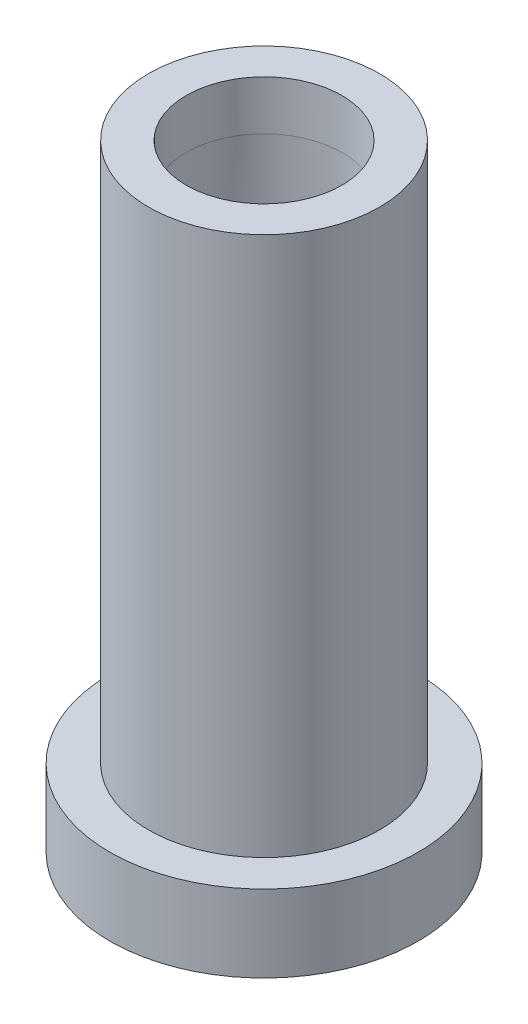
SolidWorks part; units mm, degrees
material "K110"
ref_plane "Front Plane" through (0, 0, 0) normal (0, 0, 1) x (1, 0, 0)
ref_plane "Top Plane" through (0, 0, 0) normal (0, 1, 0) x (1, 0, 0)
ref_plane "Right Plane" through (0, 0, 0) normal (1, 0, 0) x (0, 0, -1)
sketch "Sketch1" plane through (0, 0, 0) normal (0, 0, 1) x (1, 0, 0)
  line L0 (0, 0) -> (10, 0)
  line L1 (10, 0) -> (10, 5)
  line L2 (10, 5) -> (7.5, 5)
  line L3 (7.5, 5) -> (7.5, 40)
  line L4 (7.5, 40) -> (0, 40)
  line L5 (0, 40) -> (0, 0)
  line L6 (0, 45) -> (0, -5) construction
  line L7 (9.9, 0) -> (-9.9, 0) construction
  dimension "D1" = 5
  dimension "D2" = 5
  dimension "D3" = 15
  dimension "D4" = 20
  dimension "D5" = 5
  dimension "D6" = 40
revolve "Revolve1" add sketch "Sketch1" angle 360 about L6
sketch "Sketch2" plane through (0, 40, 0) normal (0, 1, 0) x (1, 0, 0)
  circle A0 centre (0, 0) radius 5.05
  dimension "D1" = 10.1
extrude "Cut-Extrude1" cut sketch "Sketch2" against normal up to next
sketch "Sketch3" plane through (0, 0, 0) normal (0, 0, 1) x (1, 0, 0)
  line L0 (5.05, 36.8) -> (6.0136, 0)
  line L1 (5.05, 0) -> (5.05, 40) construction
  line L2 (11, 0) -> (-11, 0) construction
  line L3 (6.0136, 0) -> (5.05, 0)
  line L4 (5.05, 0) -> (5.05, 36.8)
  line L5 (7.5, 40) -> (-7.5, 40) construction
  dimension "D1" = 3.2
  dimension "D2" = 1.5
sweep "Cut-Sweep1" cut profiles "Sketch3" path edge at (0, 40, 5.05)
